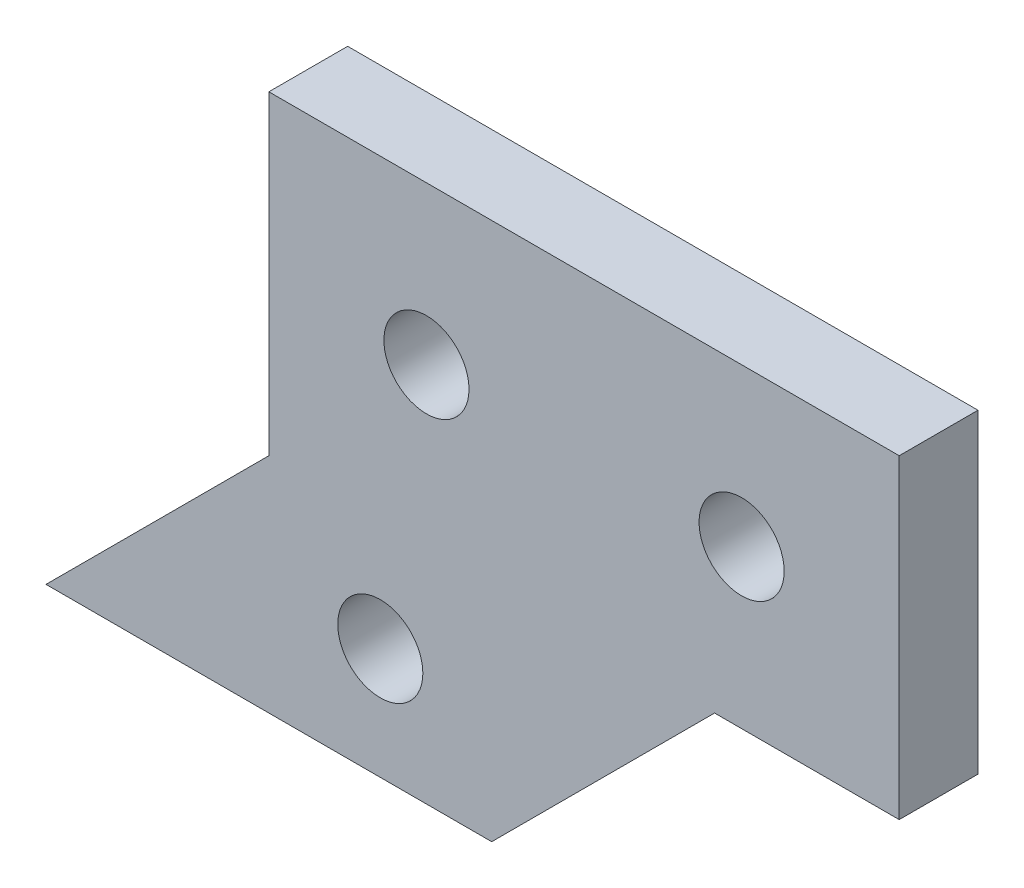
SolidWorks part; units mm, degrees
ref_plane "Front Plane" through (0, 0, 0) normal (0, 0, 1) x (1, 0, 0)
ref_plane "Top Plane" through (0, 0, 0) normal (0, 1, 0) x (1, 0, 0)
ref_plane "Right Plane" through (0, 0, 0) normal (1, 0, 0) x (0, 0, -1)
sketch "Sketch1" plane through (0, 0, 0) normal (0, 0, 1) x (1, 0, 0)
  line L0 (35.921, -25.4) -> (17.9605, -43.3605)
  line L1 (0, 0) -> (50.8, 0)
  line L2 (0, 0) -> (0, -25.4)
  line L3 (35.921, -25.4) -> (50.8, -25.4)
  line L4 (50.8, 0) -> (50.8, -25.4)
  line L5 (0, -25.4) -> (-17.9605, -43.3605)
  line L6 (-17.9605, -43.3605) -> (17.9605, -43.3605)
  line L7 (35.921, -25.4) -> (85.0059, 23.6849) construction
  line L8 (0, -12.7) -> (72.3641, -12.7) construction
  line L9 (0, -43.3605) -> (17.9934, -25.3671) construction
  line L10 (0, -25.4) -> (17.9605, -43.3605) construction
  circle A0 centre (12.7, -12.7) radius 3.429
  circle A1 centre (38.1, -12.7) radius 3.429
  circle A3 centre (8.9803, -34.3803) radius 3.429
  point P18 (-8.9803, -34.3803)
  dimension "D6" = 6.858
  dimension "D7" = 25.4
  dimension "D1" = 25.4
  dimension "D2" = 45
  dimension "D3" = 25.4
  dimension "D4" = 50.8
  dimension "D5" = 25.4
  dimension "D8" = 12.7
extrude "Boss-Extrude1" add sketch "Sketch1" along normal blind 6.35
